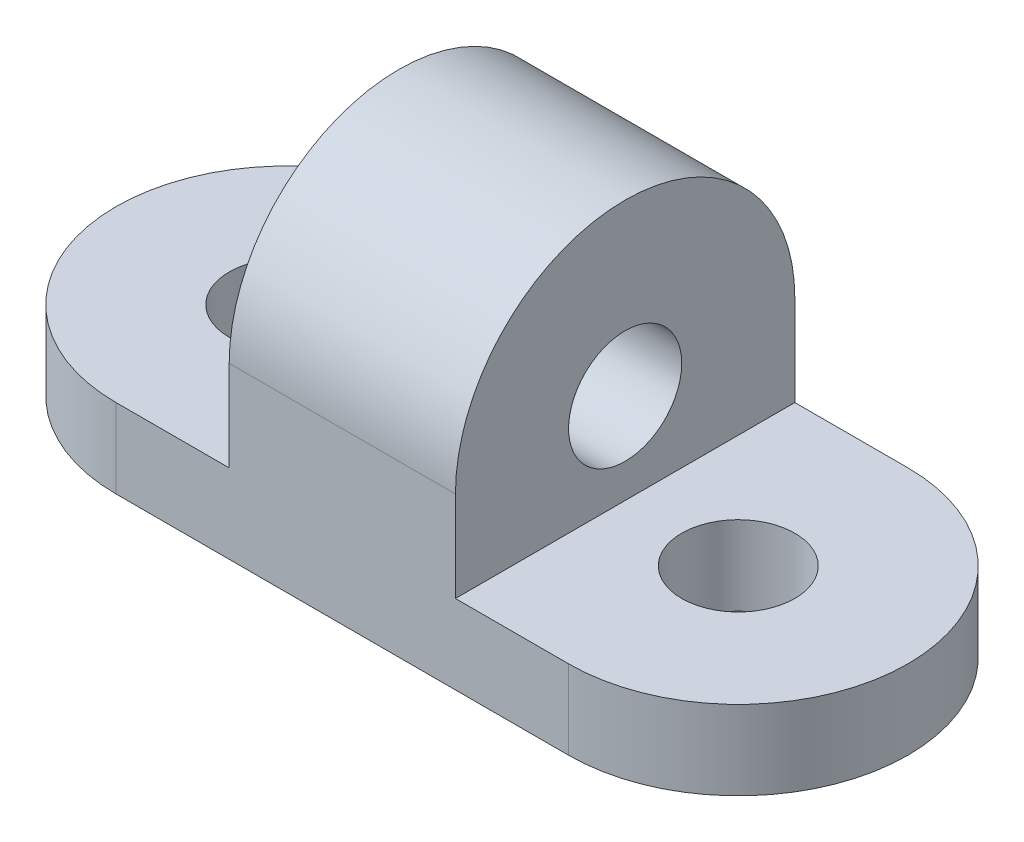
SolidWorks part; units mm, degrees
material "Copper"
ref_plane "Front Plane" through (0, 0, 0) normal (0, 0, 1) x (1, 0, 0)
ref_plane "Top Plane" through (0, 0, 0) normal (0, 1, 0) x (1, 0, 0)
ref_plane "Right Plane" through (0, 0, 0) normal (1, 0, 0) x (0, 0, -1)
sketch "Croquis1" plane through (0, 0, 0) normal (0, 1, 0) x (1, 0, 0)
  line L0 (0, 0) -> (80, 0)
  line L2 (80, 60) -> (0, 60)
  arc A0 (0, 60) -> (0, 0) centre (0, 30) ccw
  arc A1 (80, 60) -> (80, 0) centre (80, 30) cw
  circle A2 centre (0, 30) radius 10
  circle A3 centre (80, 30) radius 10
  dimension "D2" = 30
  dimension "D3" = 20
  dimension "D4" = 20
  dimension "D1" = 80
extrude "Saliente-Extruir1" add sketch "Croquis1" along normal blind 14
sketch "Croquis5" plane through (0, 0, 0) normal (1, 0, 0) x (0, 0, -1)
  line L0 (60, 14) -> (60, 30)
  line L2 (0, 30) -> (0, 14)
  line L3 (60, 14) -> (0, 14)
  arc A0 (60, 30) -> (0, 30) centre (30, 30) ccw
  circle A1 centre (30, 30) radius 10
  dimension "D2" = 20
  dimension "D1" = 16
extrude "Saliente-Extruir2" add sketch "Croquis5" along normal blind 40 from offset 20
